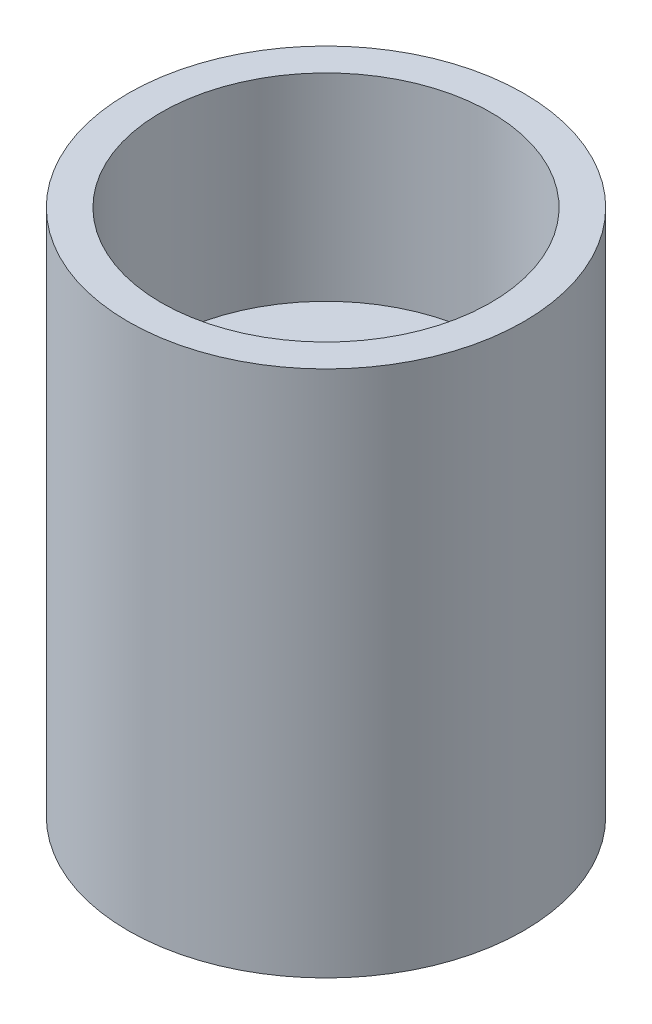
SolidWorks part; units mm, degrees
ref_plane "Front Plane" through (0, 0, 0) normal (0, 0, 1) x (1, 0, 0)
ref_plane "Top Plane" through (0, 0, 0) normal (0, 1, 0) x (1, 0, 0)
ref_plane "Right Plane" through (0, 0, 0) normal (1, 0, 0) x (0, 0, -1)
sketch "Sketch1" plane through (0, 0, 0) normal (0, 1, 0) x (1, 0, 0)
  circle A0 centre (0, 0) radius 3
  dimension "D1" = 6
extrude "Boss-Extrude1" add sketch "Sketch1" along normal blind 8
sketch "Sketch2" plane through (0, 8, 0) normal (0, 1, 0) x (1, 0, 0)
  circle A0 centre (0, 0) radius 2.5
  dimension "D1" = 5
extrude "Cut-Extrude1" cut sketch "Sketch2" against normal blind 3
sketch "Sketch3" plane through (0, 0, 0) normal (0, -1, 0) x (1, 0, 0)
  circle A0 centre (0, 0) radius 2.5
  dimension "D1" = 5
extrude "Cut-Extrude2" cut sketch "Sketch3" against normal blind 3
